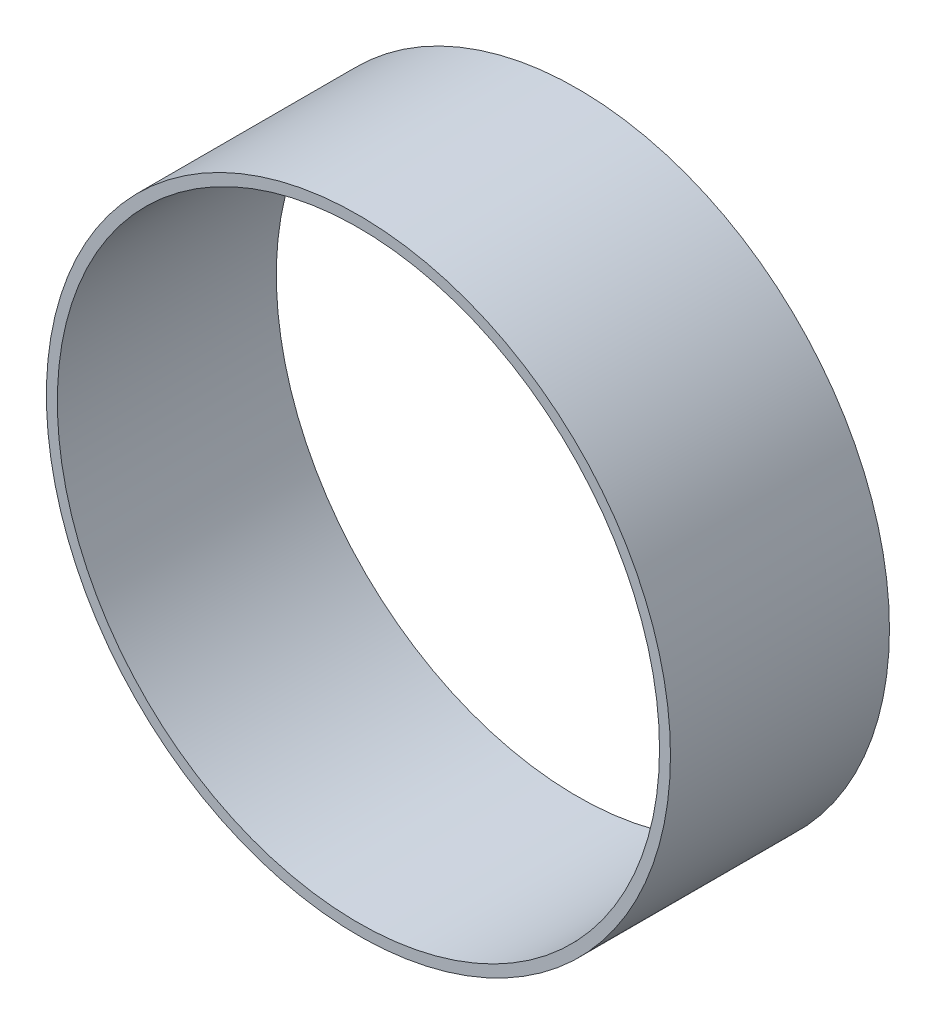
SolidWorks part; units mm, degrees
ref_plane "Front Plane" through (0, 0, 0) normal (0, 0, 1) x (1, 0, 0)
ref_plane "Top Plane" through (0, 0, 0) normal (0, 1, 0) x (1, 0, 0)
ref_plane "Right Plane" through (0, 0, 0) normal (1, 0, 0) x (0, 0, -1)
sketch "Sketch1" plane through (0, 0, 0) normal (0, 0, 1) x (1, 0, 0)
  circle A0 centre (0, 0) radius 55
  circle A1 centre (0, 0) radius 57
  dimension "D1" = 110
  dimension "D2" = 2
extrude "Boss-Extrude1" add sketch "Sketch1" along normal blind 40
